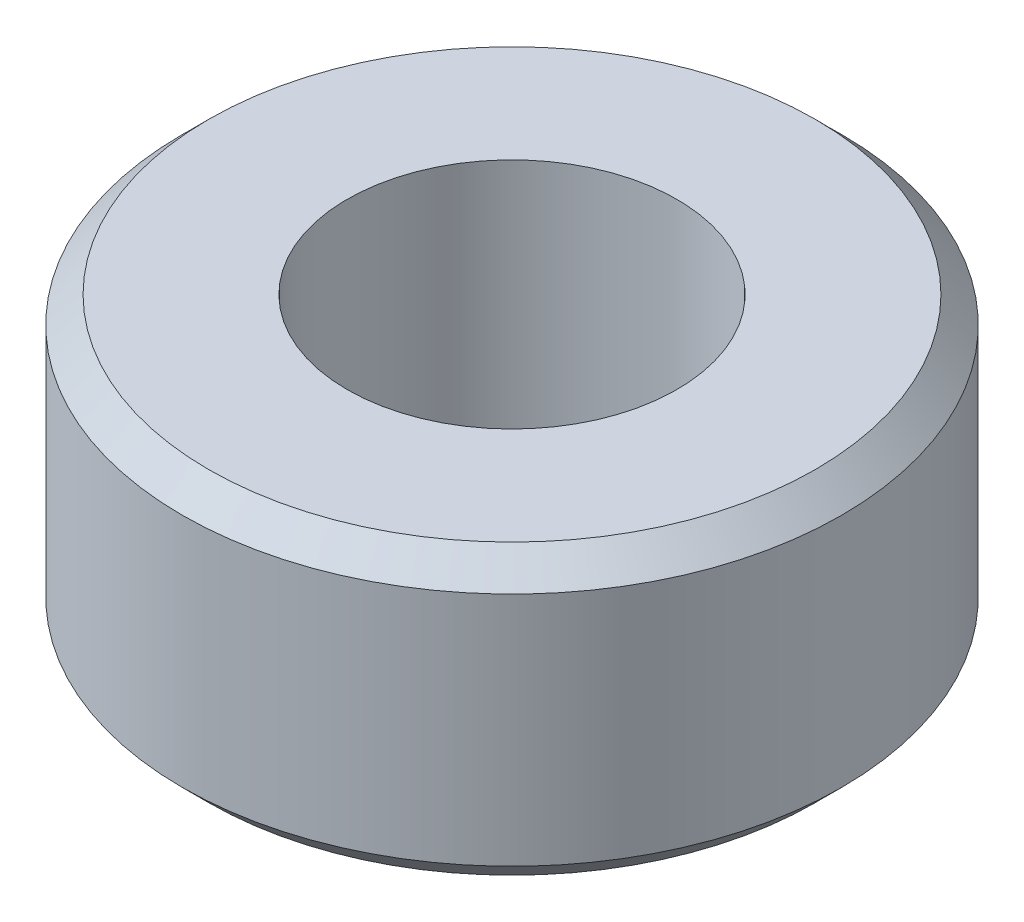
SolidWorks part; units mm, degrees
ref_plane "Front Plane" through (0, 0, 0) normal (0, 0, 1) x (1, 0, 0)
ref_plane "Top Plane" through (0, 0, 0) normal (0, 1, 0) x (1, 0, 0)
ref_plane "Right Plane" through (0, 0, 0) normal (1, 0, 0) x (0, 0, -1)
sketch "Sketch1" plane through (0, 0, 0) normal (0, 1, 0) x (1, 0, 0)
  circle A0 centre (0, 0) radius 1.5875
  circle A1 centre (0, 0) radius 3.175
  dimension "D1" = 3.175
  dimension "D2" = 6.35
extrude "Boss-Extrude1" add sketch "Sketch1" along normal blind 2.7781
chamfer "Chamfer1" distance 0.254 distance2 0.254 2 edges at (0, 0, 3.175) (0, 2.7781, 3.175)
